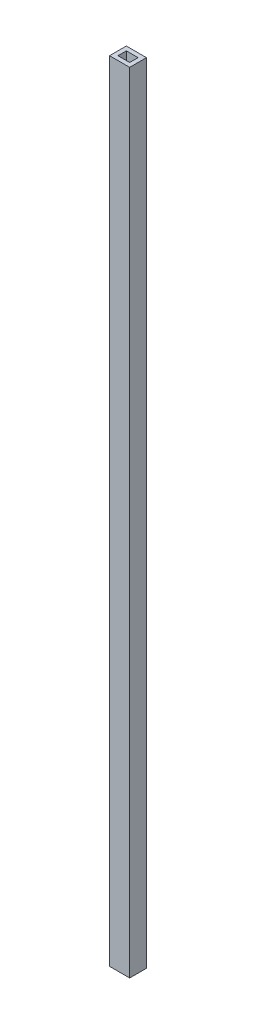
SolidWorks part; units mm, degrees
material "Acrylique (impact moyen-haut)"
ref_plane "Plan de face" through (0, 0, 0) normal (0, 0, 1) x (1, 0, 0)
ref_plane "Plan de dessus" through (0, 0, 0) normal (0, 1, 0) x (1, 0, 0)
ref_plane "Plan de droite" through (0, 0, 0) normal (1, 0, 0) x (0, 0, -1)
sketch "Esquisse1" plane through (0, 0, 0) normal (0, 1, 0) x (1, 0, 0)
  line L0 (-4.445, 3.175) -> (4.445, 3.175)
  line L1 (-7.62, -6.35) -> (7.62, -6.35)
  line L2 (-7.62, -6.35) -> (-7.62, 6.35)
  line L3 (-7.62, 6.35) -> (7.62, 6.35)
  line L4 (7.62, -6.35) -> (7.62, 6.35)
  line L5 (-7.62, -6.35) -> (7.62, 6.35) construction
  line L6 (-7.62, 6.35) -> (7.62, -6.35) construction
  line L7 (4.445, -3.175) -> (4.445, 3.175)
  line L8 (-4.445, -3.175) -> (4.445, -3.175)
  line L9 (-4.445, -3.175) -> (-4.445, 3.175)
  point P0 (0, 0)
  dimension "D1" = 12.7
  dimension "D2" = 15.24
  dimension "D3" = 3.175
extrude "Boss.-Extru.1" add sketch "Esquisse1" along normal blind 596.9
